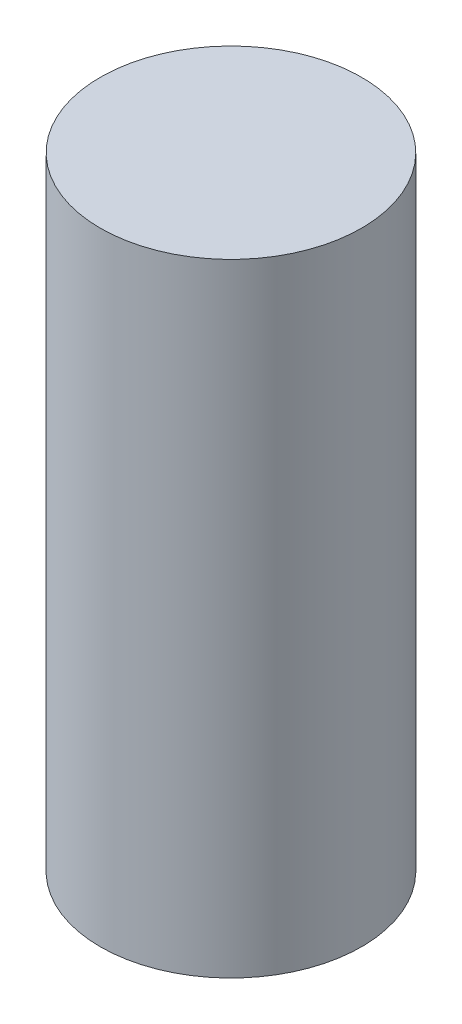
SolidWorks part; units mm, degrees
ref_plane "Front Plane" through (0, 0, 0) normal (0, 0, 1) x (1, 0, 0)
ref_plane "Top Plane" through (0, 0, 0) normal (0, 1, 0) x (1, 0, 0)
ref_plane "Right Plane" through (0, 0, 0) normal (1, 0, 0) x (0, 0, -1)
sketch "Sketch1" plane through (0, 0, 0) normal (0, 1, 0) x (1, 0, 0)
  line L0 (-10.5, 0) -> (10.5, 0) construction
  line L1 (0, 10.5) -> (0, -10.5) construction
  circle A0 centre (0, 0) radius 10.5
  dimension "D1" = 21
extrude "Boss-Extrude1" add sketch "Sketch1" along normal blind 50
